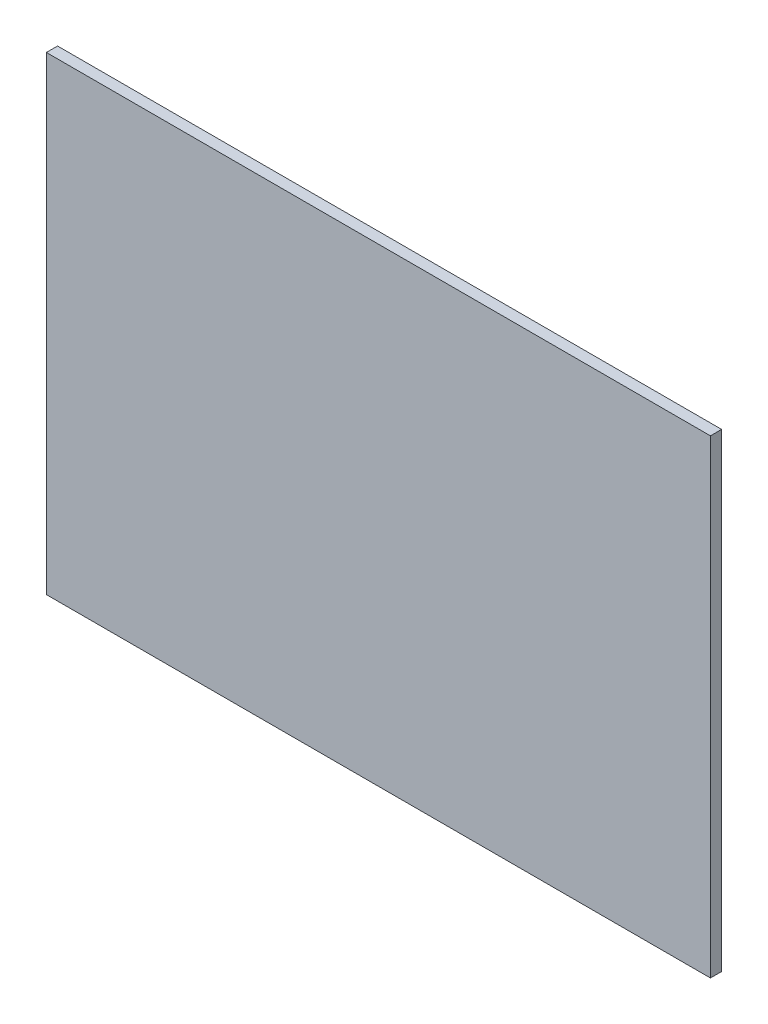
SolidWorks part; units mm, degrees
ref_plane "Front Plane" through (0, 0, 0) normal (0, 0, 1) x (1, 0, 0)
ref_plane "Top Plane" through (0, 0, 0) normal (0, 1, 0) x (1, 0, 0)
ref_plane "Right Plane" through (0, 0, 0) normal (1, 0, 0) x (0, 0, -1)
sketch "Sketch1" plane through (0, 0, 0) normal (0, 0, 1) x (1, 0, 0)
  line L1 (0, 0) -> (-297, 0)
  line L2 (0, 0) -> (0, -210)
  line L3 (0, -210) -> (-297, -210)
  line L4 (-297, 0) -> (-297, -210)
  dimension "D1" = 210
  dimension "D2" = 297
extrude "Boss-Extrude1" add sketch "Sketch1" along normal blind 5
